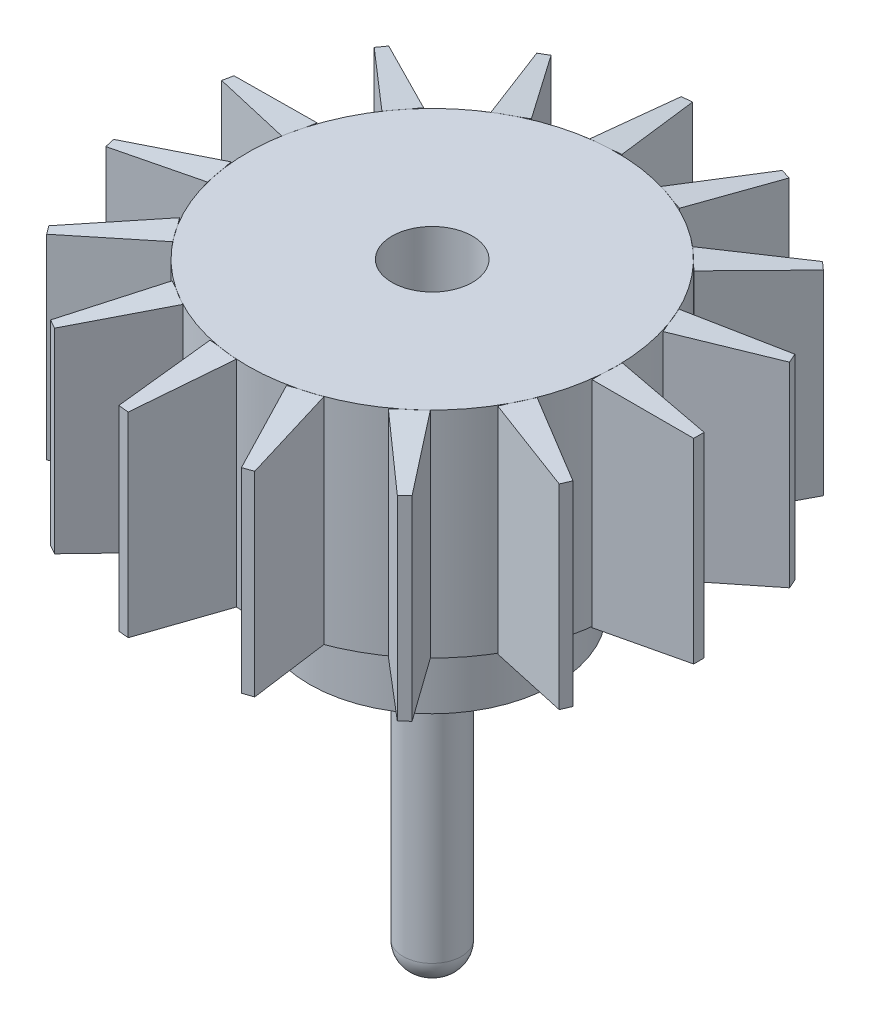
SolidWorks part; units mm, degrees
ref_plane "Front Plane" through (0, 0, 0) normal (0, 0, 1) x (1, 0, 0)
ref_plane "Top Plane" through (0, 0, 0) normal (0, 1, 0) x (1, 0, 0)
ref_plane "Right Plane" through (0, 0, 0) normal (1, 0, 0) x (0, 0, -1)
sketch "Sketch1" plane through (0, 0, 0) normal (0, 1, 0) x (1, 0, 0)
  circle A0 centre (0, 0) radius 40.4653
  circle A1 centre (0, 0) radius 60.1972
extrude "Boss-Extrude1" add sketch "Sketch1" along normal blind 70
ref_plane "Plane2" through (60, 0, 0) normal (1, 0, 0) x (0, 0, -1)
sketch "Sketch3" plane through (60, 0, 0) normal (1, 0, 0) x (0, 0, -1)
  line L0 (60.1972, 70) -> (-60.1972, 70) construction
  line L1 (-7.9444, 70) -> (1.7654, 70)
  line L2 (-7.9444, 70) -> (-7.9444, 0)
  line L3 (-7.9444, 0) -> (1.7654, 0)
  line L4 (1.7654, 70) -> (1.7654, 0)
extrude "Boss-Extrude2" add sketch "Sketch3" along normal blind 30 draft 6
sketch "Sketch4" plane through (90, 0, 0) normal (1, 0, 0) x (0, 0, -1)
  line L0 (-1.3877, 3.1531) -> (-1.3877, 66.8469) construction
  line L1 (-4.7913, 66.8469) -> (-1.3877, 66.8469)
  line L2 (-4.7913, 66.8469) -> (-4.7913, 3.3992)
  line L3 (-4.7913, 3.3992) -> (-1.3877, 3.3992)
  line L4 (-1.3877, 66.8469) -> (-1.3877, 3.3992)
pattern_circular "CirPattern2" count 15 over 337 about axis through (0, 0, 0) along (0, 1, 0) of "Boss-Extrude2"
sketch "Sketch5" plane through (0, 0, 0) normal (0, -1, 0) x (1, 0, 0)
  circle A0 centre (0, 0) radius 42.6466
  circle A1 centre (0, 0) radius 13.1
extrude "Boss-Extrude3" add sketch "Sketch5" against normal blind 70
sketch "Sketch6" plane through (0, 0, 0) normal (0, -1, 0) x (1, 0, 0)
  circle A0 centre (0, 0) radius 40
extrude "Boss-Extrude4" add sketch "Sketch6" along normal blind 30
sketch "Sketch7" plane through (0, -30, 0) normal (0, -1, 0) x (1, 0, 0)
  circle A0 centre (0, 0) radius 9.525
extrude "Boss-Extrude5" add sketch "Sketch7" along normal blind 100
fillet "Fillet2" radius 8 1 edges at (0, -130, -9.525)
